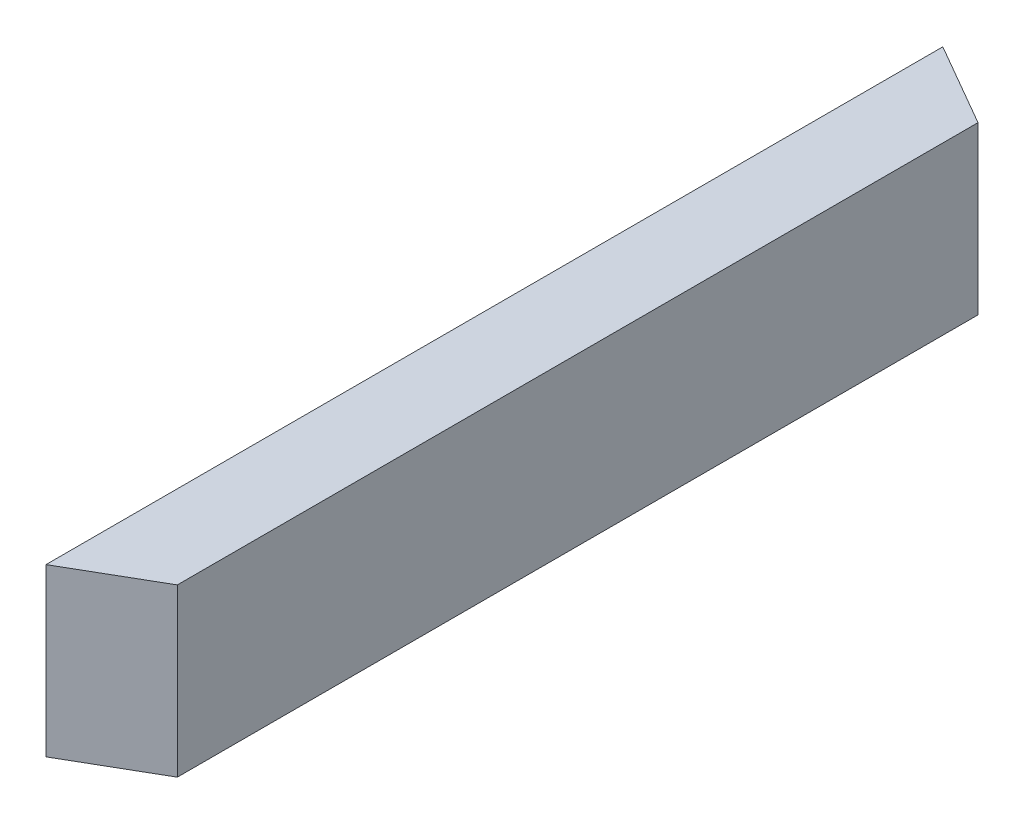
SolidWorks part; units mm, degrees
ref_plane "Front Plane" through (0, 0, 0) normal (0, 0, 1) x (1, 0, 0)
ref_plane "Top Plane" through (0, 0, 0) normal (0, 1, 0) x (1, 0, 0)
ref_plane "Right Plane" through (0, 0, 0) normal (1, 0, 0) x (0, 0, -1)
sketch "Sketch1" plane through (0, 0, 0) normal (0, 0, 1) x (1, 0, 0)
  line L1 (0, 0) -> (-44.45, 0)
  line L2 (0, 0) -> (0, 88.9)
  line L3 (0, 88.9) -> (-44.45, 88.9)
  line L4 (-44.45, 0) -> (-44.45, 88.9)
  dimension "D1" = 88.9
  dimension "D2" = 44.45
extrude "Boss-Extrude1" add sketch "Sketch1" along normal blind 478.79
sketch "Sketch2" plane through (0, 88.9, 0) normal (0, 1, 0) x (1, 0, 0)
  line L0 (-44.45, 0) -> (0, -25.6632)
  line L1 (0, -478.79) -> (0, 0) construction
  line L2 (0, -25.6632) -> (0, 0)
  line L3 (0, 0) -> (-44.45, 0)
  line L4 (-44.45, -478.79) -> (0, -453.1268)
  line L5 (0, -453.1268) -> (0, -478.79)
  line L6 (0, -478.79) -> (-44.45, -478.79)
  line L7 (0, -478.79) -> (-44.45, -504.4532)
  line L8 (-44.45, -504.4532) -> (-44.45, -478.79)
  dimension "D1" = 30
  dimension "D2" = 60
extrude "Cut-Extrude1" cut sketch "Sketch2" against normal blind 478.79 contours L3 L0 L2 | L6 L4 L5
